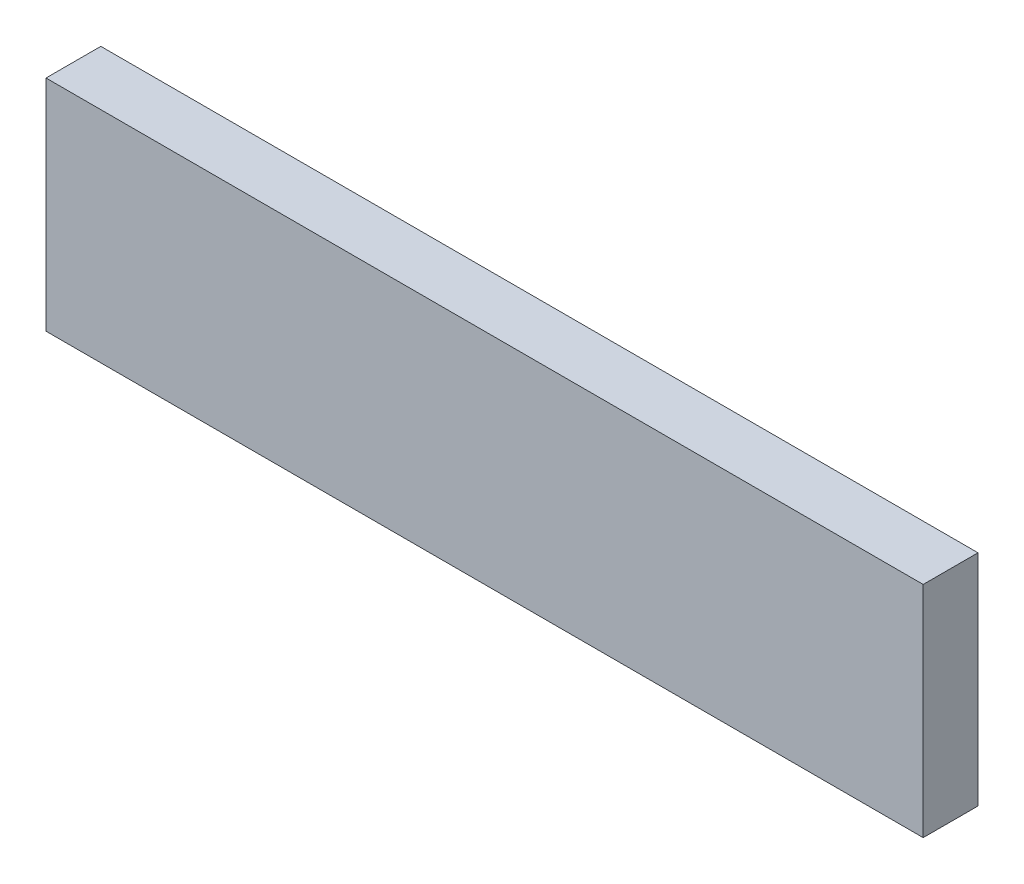
SolidWorks part; units mm, degrees
material "AISI 1035 Steel (SS)"
ref_plane "Front Plane" through (0, 0, 0) normal (0, 0, 1) x (1, 0, 0)
ref_plane "Top Plane" through (0, 0, 0) normal (0, 1, 0) x (1, 0, 0)
ref_plane "Right Plane" through (0, 0, 0) normal (1, 0, 0) x (0, 0, -1)
sketch "Sketch1" plane through (0, 0, 0) normal (0, 0, 1) x (1, 0, 0)
  line L1 (-50.8, -12.7) -> (50.8, -12.7)
  line L2 (-50.8, -12.7) -> (-50.8, 12.7)
  line L3 (-50.8, 12.7) -> (50.8, 12.7)
  line L4 (50.8, -12.7) -> (50.8, 12.7)
  line L5 (-50.8, -12.7) -> (50.8, 12.7) construction
  line L6 (-50.8, 12.7) -> (50.8, -12.7) construction
  point P0 (0, 0)
  dimension "D1" = 25.4
  dimension "D2" = 101.6
extrude "Boss-Extrude1" add sketch "Sketch1" along normal blind 6.35
